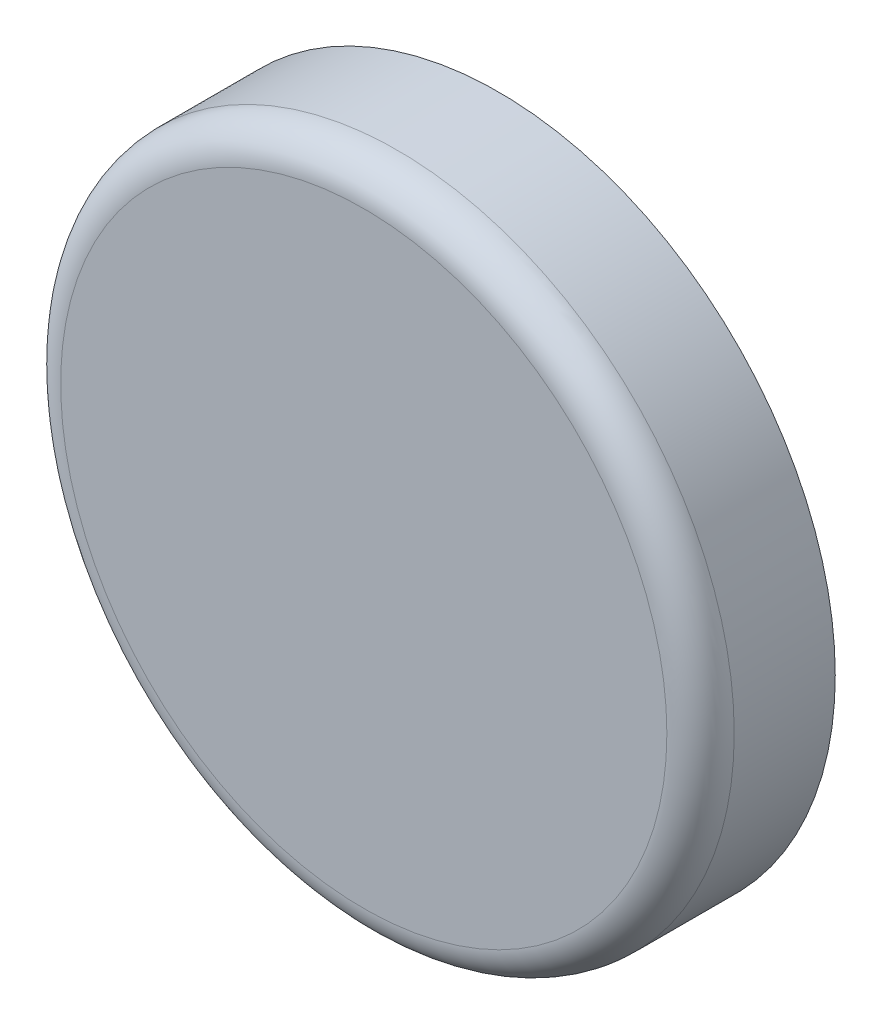
SolidWorks part; units mm, degrees
ref_plane "Front Plane" through (0, 0, 0) normal (0, 0, 1) x (1, 0, 0)
ref_plane "Top Plane" through (0, 0, 0) normal (0, 1, 0) x (1, 0, 0)
ref_plane "Right Plane" through (0, 0, 0) normal (1, 0, 0) x (0, 0, -1)
sketch "Sketch3" plane through (0, 0, 0) normal (0, 0, 1) x (1, 0, 0)
  circle A0 centre (0, 0) radius 5
  dimension "D1" = 10
extrude "Boss-Extrude1" add sketch "Sketch3" along normal blind 2
fillet "Fillet1" radius 0.5 1 edges at (5, 0, 2)
